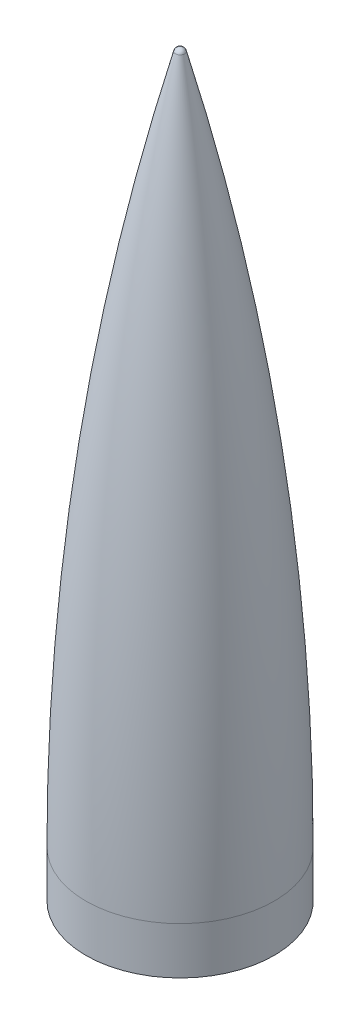
SolidWorks part; units mm, degrees
ref_plane "Front Plane" through (0, 0, 0) normal (0, 0, 1) x (1, 0, 0)
ref_plane "Top Plane" through (0, 0, 0) normal (0, 1, 0) x (1, 0, 0)
ref_plane "Right Plane" through (0, 0, 0) normal (1, 0, 0) x (0, 0, -1)
sketch "Sketch2" plane through (0, 0, 0) normal (0, 0, 1) x (1, 0, 0)
  line L0 (40, 0) -> (40, -20)
  line L1 (0, 294.2738) -> (0, 0) construction
  line L2 (40, -20) -> (38, -20)
  line L3 (38, -20) -> (38, 0)
  line L4 (0, 294.2738) -> (0, 292.2738)
  line L5 (0, 300) -> (0, 294.2738) construction
  line L6 (0, 300) -> (0, 294.2738) construction
  arc A0 (40, 0) -> (1.9335, 292.7853) centre (-1105, 0) ccw
  arc A1 (38, 0) -> (0, 292.2738) centre (-1105, 0) ccw
  arc A2 (38, 0) -> (-1.9301, 299.476) centre (-1105, 0) ccw construction
  arc A3 (1.9335, 292.7853) -> (0, 294.2738) centre (0, 292.2738) ccw
  arc A4 (1.9335, 292.7853) -> (0, 300) centre (-1105, 0) ccw construction
  arc A5 (40, 0) -> (0, 300) centre (-1105, 0) ccw construction
  dimension "D1" = 40
  dimension "D2" = 20
  dimension "D3" = 300
  dimension "D4" = 2
revolve "Revolve1" add sketch "Sketch2" angle 360 about L1
